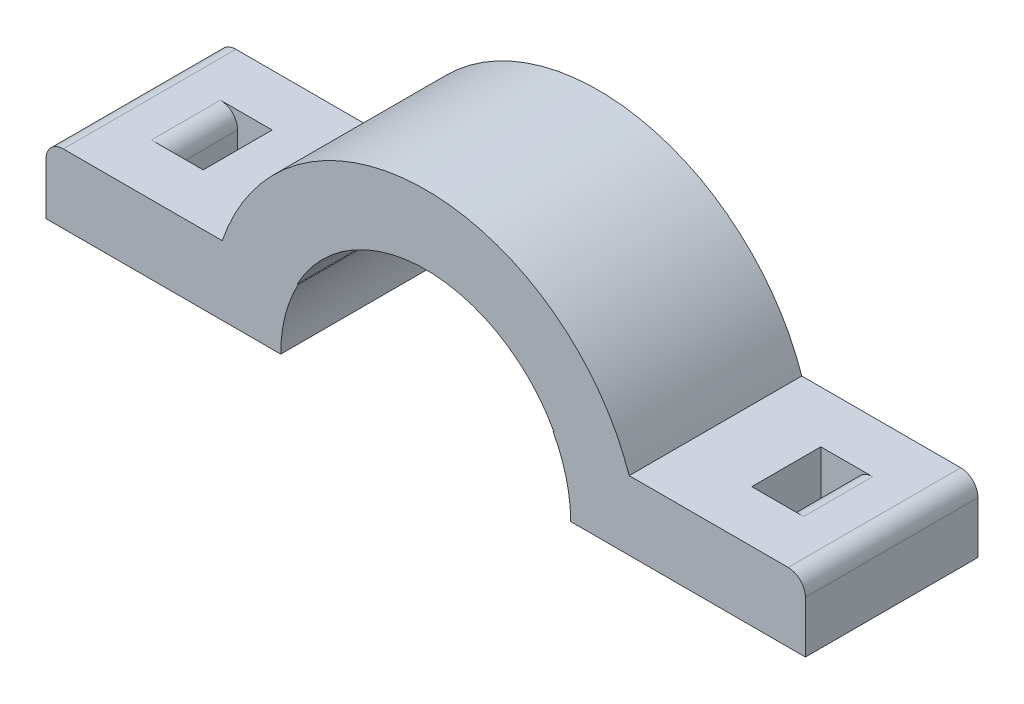
SolidWorks part; units mm, degrees
ref_plane "Front Plane" through (0, 0, 0) normal (0, 0, 1) x (1, 0, 0)
ref_plane "Top Plane" through (0, 0, 0) normal (0, 1, 0) x (1, 0, 0)
ref_plane "Right Plane" through (0, 0, 0) normal (1, 0, 0) x (0, 0, -1)
sketch "Sketch2" plane through (0, 0, 0) normal (0, 0, 1) x (1, 0, 0)
  line L0 (-15.8115, 0) -> (-10.7315, 0)
  line L1 (10.7315, 0) -> (15.8115, 0)
  arc A0 (10.7315, 0) -> (-10.7315, 0) centre (0, 0) ccw
  arc A1 (15.8115, 0) -> (-15.8115, 0) centre (0, 0) ccw
  circle A2 centre (0, 0) radius 10.7315 construction
  circle A3 centre (0, 0) radius 15.8115 construction
  dimension "D1" = 21.463
  dimension "D2" = 5.08
extrude "Boss-Extrude1" add sketch "Sketch2" along normal blind 12.7
sketch "Sketch3" plane through (0, 0, 0) normal (1, 0, 0) x (0, 0, -1)
  line L0 (0, 0) -> (0, 15.8115) construction
  line L1 (-12.7, 0) -> (0, 0)
  line L2 (-12.7, 0) -> (-12.7, 5.08)
  line L3 (-12.7, 5.08) -> (0, 5.08)
  line L4 (0, 0) -> (0, 5.08)
  dimension "D1" = 5.08
extrude "Boss-Extrude2" add sketch "Sketch3" along normal mid plane 55.88
sketch "Sketch4" plane through (0, 0, 12.7) normal (0, 0, 1) x (1, 0, 0)
  circle A0 centre (0, 0) radius 10.668
  dimension "D1" = 21.336
extrude "Cut-Extrude1" cut sketch "Sketch4" against normal blind 44.196
sketch "Sketch6" plane through (0, 0, 0) normal (0, -1, 0) x (1, 0, 0)
  line L0 (-27.94, 6.35) -> (27.94, 6.35) construction
  line L1 (-27.94, 12.7) -> (-27.94, 0) construction
  line L2 (27.94, 12.7) -> (27.94, 0) construction
  line L3 (-21.4566, 0) -> (-21.4566, 12.7) construction
  line L6 (-14.9732, 0) -> (-27.94, 0) construction
  line L9 (-14.9732, 12.7) -> (-27.94, 12.7) construction
  line L10 (21.4566, 0) -> (21.4566, 12.7) construction
  line L11 (27.94, 0) -> (14.9732, 0) construction
  line L12 (27.94, 12.7) -> (14.9732, 12.7) construction
  line L14 (-22.7266, 3.81) -> (-20.1866, 3.81)
  line L15 (-22.7266, 3.81) -> (-22.7266, 8.89)
  line L16 (-22.7266, 8.89) -> (-20.1866, 8.89)
  line L17 (-20.1866, 3.81) -> (-20.1866, 8.89)
  line L18 (-22.7266, 3.81) -> (-20.1866, 8.89) construction
  line L19 (-22.7266, 8.89) -> (-20.1866, 3.81) construction
  line L20 (20.1866, 3.81) -> (22.7266, 3.81)
  line L21 (20.1866, 3.81) -> (20.1866, 8.89)
  line L22 (20.1866, 8.89) -> (22.7266, 8.89)
  line L23 (22.7266, 3.81) -> (22.7266, 8.89)
  line L24 (20.1866, 3.81) -> (22.7266, 8.89) construction
  line L25 (20.1866, 8.89) -> (22.7266, 3.81) construction
  point P6 (-21.4566, 6.35)
  point P23 (21.4566, 6.35)
  dimension "D1" = 5.08
  dimension "D2" = 2.54
extrude "Cut-Extrude3" cut sketch "Sketch6" against normal up to next
fillet "Fillet1" radius 1.27 4 edges at (-22.7266, 5.08, 6.35) (22.7266, 5.08, 6.35) (27.94, 5.08, 6.35) (-27.94, 5.08, 6.35)
